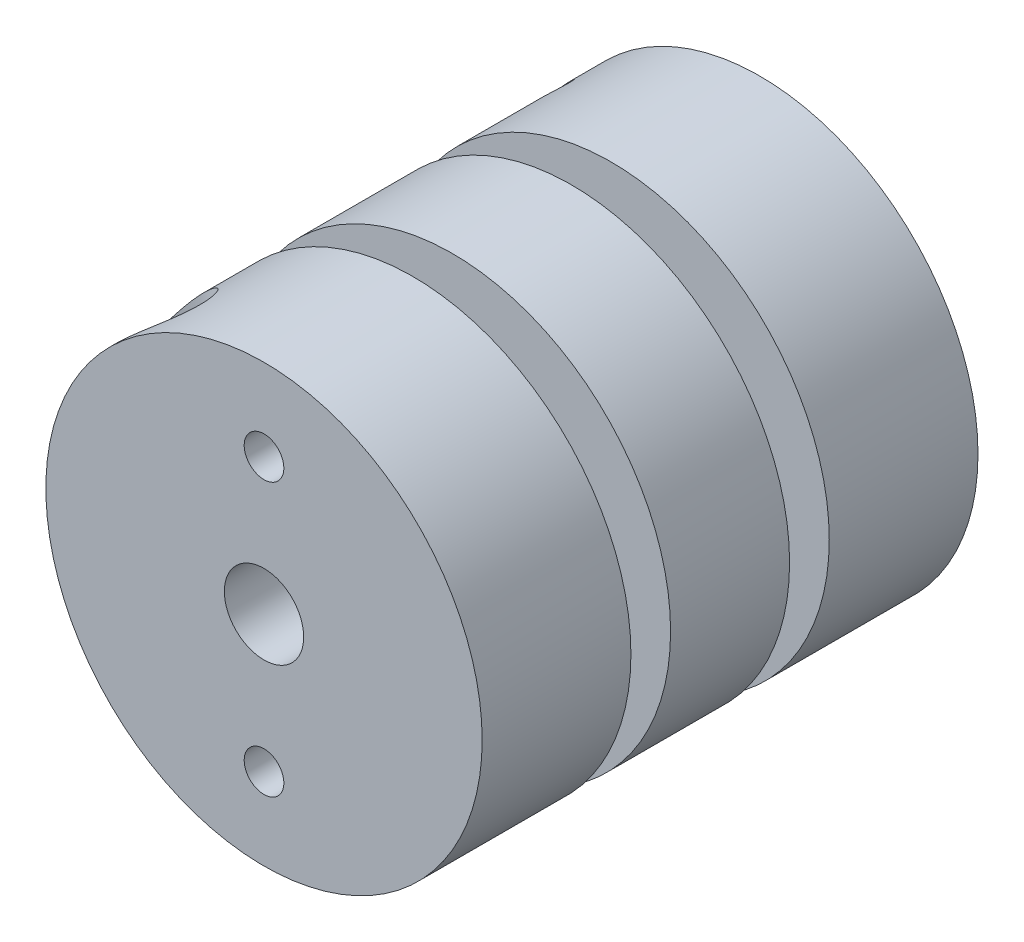
SolidWorks part; units mm, degrees
ref_plane "前视基准面" through (0, 0, 0) normal (0, 0, 1) x (1, 0, 0)
ref_plane "上视基准面" through (0, 0, 0) normal (0, 1, 0) x (1, 0, 0)
ref_plane "右视基准面" through (0, 0, 0) normal (1, 0, 0) x (0, 0, -1)
sketch "草图1" plane through (0, 0, 0) normal (0, 0, 1) x (1, 0, 0)
  circle A0 centre (0, 0) radius 22
  dimension "D1" = 44
extrude "凸台-拉伸1" add sketch "草图1" along normal mid plane 12
sketch "草图2" plane through (0, 0, 0) normal (0, 0, 1) x (1, 0, 0)
  circle A0 centre (0, 0) radius 15
  dimension "D1" = 30
extrude "凸台-拉伸2" add sketch "草图2" along normal mid plane 20
sketch "草图3" plane through (0, 0, 10) normal (0, 0, 1) x (1, 0, 0)
  line L0 (0, 0) -> (0, 10.78) construction
  line L1 (0, 0) -> (7.3126, 0) construction
  circle A0 centre (0, 0) radius 22 construction
  circle A1 centre (0, 0) radius 22
  circle A2 centre (0, 13.75) radius 2
  circle A3 centre (0, -13.75) radius 2
  dimension "D1" = 27.5
  dimension "D2" = 4
extrude "凸台-拉伸3" add sketch "草图3" along normal blind 15
sketch "草图4" plane through (0, 0, 0) normal (0, 1, 0) x (1, 0, 0)
  line L0 (-22, -10) -> (-22, -25) construction
  line L1 (-22, -25) -> (22, -25) construction
  circle A0 centre (-16, -20) radius 1.5
  dimension "D1" = 3
  dimension "D2" = 6
  dimension "D3" = 5
extrude "切除-拉伸1" cut sketch "草图4" against normal through all
sketch "草图5" plane through (0, 0, 0) normal (0, 1, 0) x (1, 0, 0)
  circle A0 centre (-16, -20) radius 4.5
  dimension "D1" = 9
extrude "切除-拉伸2" cut sketch "草图5" along normal through all
hole_wizard "M4 螺纹孔1" positions "草图6" profile "草图7" tap size "M4" standard "GB" end condition through all
sketch "草图6" plane through (0, 0, 0) normal (0, 1, 0) x (1, 0, 0)
  point P0 (-16, -20)
sketch "草图7" plane through (-16, 0, 20) normal (1, 0, 0) x (0, 0, 1)
  line L0 (0, 0) -> (0, 22)
  line L1 (0, 22) -> (1.65, 22)
  line L2 (1.65, 22) -> (1.65, 0.375)
  line L3 (1.65, 0.375) -> (2.025, 0)
  line L5 (2.025, 0) -> (0, 0)
  line L6 (-1.65, 0.375) -> (-2.025, 0) construction
  line L11 (0, -6.35) -> (0, 107.95) construction
  dimension "通孔螺纹孔钻头直径" = 3.3
  dimension "通孔螺纹孔钻头深度" = 22
  dimension "近端锥形沉头孔直径" = 4.05
  dimension "近端锥形沉头孔角度" = 90
cosmetic thread "孔螺蚊线1" parameters "D2"=4
mirror "镜向1" about plane through (0, 0, 0) normal (0, 0, 1) of "凸台-拉伸3"
sketch "草图8" plane through (0, 0, 0) normal (0, 1, 0) x (1, 0, 0)
  line L0 (0, 0) -> (-42.9268, 0) construction
  line L1 (-24.2, 0) -> (24.2, 0) construction
  circle A0 centre (-16, -20) radius 1.5 construction
  circle A1 centre (-16, -20) radius 1.5 construction
  circle A2 centre (-16, 20) radius 1.5
extrude "切除-拉伸3" cut sketch "草图8" along normal through all
sketch "草图9" plane through (0, 0, 0) normal (0, 1, 0) x (1, 0, 0)
  circle A0 centre (-16, 20) radius 4.5
  dimension "D1" = 9
extrude "切除-拉伸4" cut sketch "草图9" against normal through all
hole_wizard "M4 螺纹孔2" positions "3D草图1" profile "草图10" tap size "M4" standard "GB" end condition through all
sketch3d "3D草图1"
  line L0 (-16, 14.9696, -20) -> (-16, 0, -20) construction
  point P0 (-16, 0, -20)
sketch "草图10" plane through (-16, 0, -20) normal (1, 0, 0) x (0, 0, -1)
  line L0 (0, 0) -> (0, 22)
  line L1 (0, 22) -> (1.65, 22)
  line L2 (1.65, 22) -> (1.65, 0.375)
  line L3 (1.65, 0.375) -> (2.025, 0)
  line L5 (2.025, 0) -> (0, 0)
  line L6 (-1.65, 0.375) -> (-2.025, 0) construction
  line L11 (0, -6.35) -> (0, 107.95) construction
  dimension "通孔螺纹孔钻头直径" = 3.3
  dimension "通孔螺纹孔钻头深度" = 22
  dimension "近端锥形沉头孔直径" = 4.05
  dimension "近端锥形沉头孔角度" = 90
cosmetic thread "孔螺蚊线2" parameters "D2"=4
sketch "草图11" plane through (0, 0, 25) normal (0, 0, 1) x (1, 0, 0)
  circle A0 centre (0, 0) radius 4
  dimension "D1" = 8
extrude "切除-拉伸5" cut sketch "草图11" against normal up to surface (15 mm away) up to face at (22, 0, 10)
sketch "草图12" plane through (0, 0, -25) normal (0, 0, -1) x (-1, 0, 0)
  circle A0 centre (0, 0) radius 5
  dimension "D1" = 10
extrude "切除-拉伸6" cut sketch "草图12" against normal up to surface (15 mm away) up to face at (0, 0, -10)
sketch "草图13" plane through (0, 0, 0) normal (0, 0, 1) x (1, 0, 0)
  circle A0 centre (0, 0) radius 10
  dimension "D1" = 20
extrude "切除-拉伸7" cut sketch "草图13" against normal mid plane 20
